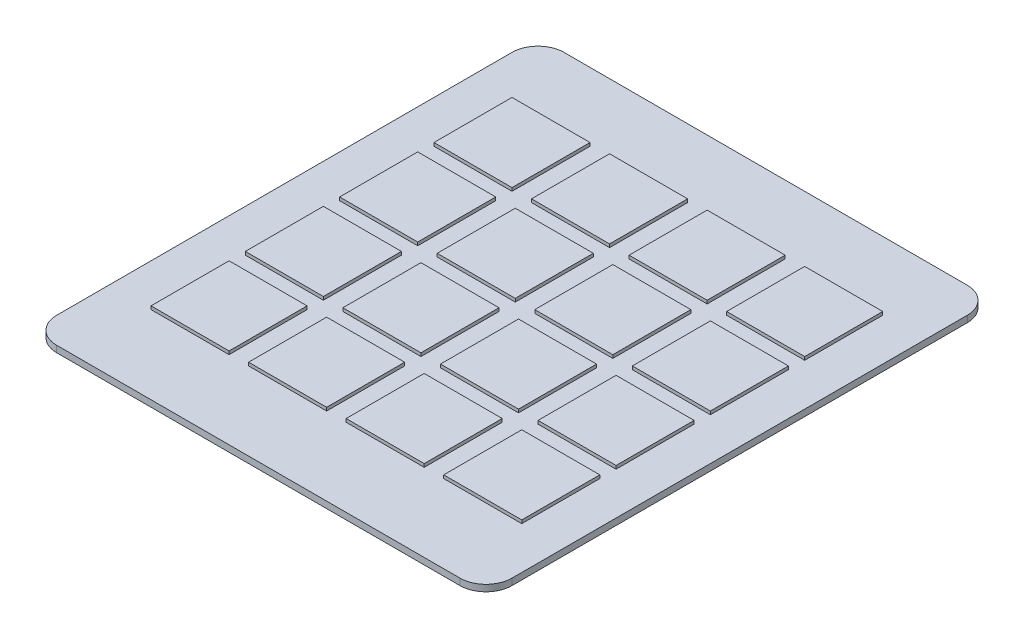
SolidWorks part; units mm, degrees
ref_plane "Ebene vorne" through (0, 0, 0) normal (0, 0, 1) x (1, 0, 0)
ref_plane "Ebene oben" through (0, 0, 0) normal (0, 1, 0) x (1, 0, 0)
ref_plane "Ebene rechts" through (0, 0, 0) normal (1, 0, 0) x (0, 0, -1)
ref_plane "Ebene1" through (0, 1, 0) normal (0, 1, 0) x (1, 0, 0)
sketch "Skizze2" plane through (0, 1, 0) normal (0, 1, 0) x (1, 0, 0)
  line L0 (169.5146, 127.8055) -> (247.5751, 69.5971) construction
  line L2 (0, 0) -> (70, 0)
  line L3 (0, 0) -> (0, 78)
  line L4 (0, 78) -> (70, 78)
  line L5 (70, 0) -> (70, 78)
  dimension "D1" = 78
  dimension "D2" = 70
extrude "Aufsatz-Linear austragen1" add sketch "Skizze2" against normal blind 1
sketch "Skizze3" plane through (0, 1, 0) normal (0, 1, 0) x (1, 0, 0)
  line L0 (67.8333, 227) -> (339.1667, 227) construction
  line L2 (6.5, 12) -> (18.5, 12)
  line L3 (6.5, 12) -> (6.5, 24)
  line L4 (6.5, 24) -> (18.5, 24)
  line L5 (18.5, 12) -> (18.5, 24)
  dimension "D1" = 12
  dimension "D2" = 12
  dimension "D3" = 12
  dimension "D4" = 6.5
extrude "Aufsatz-Linear austragen2" add sketch "Skizze3" along normal blind 0.5 separate body contours L4 L5 L2 L3
pattern_linear "Lineares Muster1" count 4 spacing 14.5 along (0, 0, -1) count 4 spacing 15 along (1, 0, 0) of bodies 102
fillet "Verrundung1" radius 4 4 edges at (0, 0.5, 0) (0, 0.5, -78) (70, 0.5, -78) (70, 0.5, 0)
